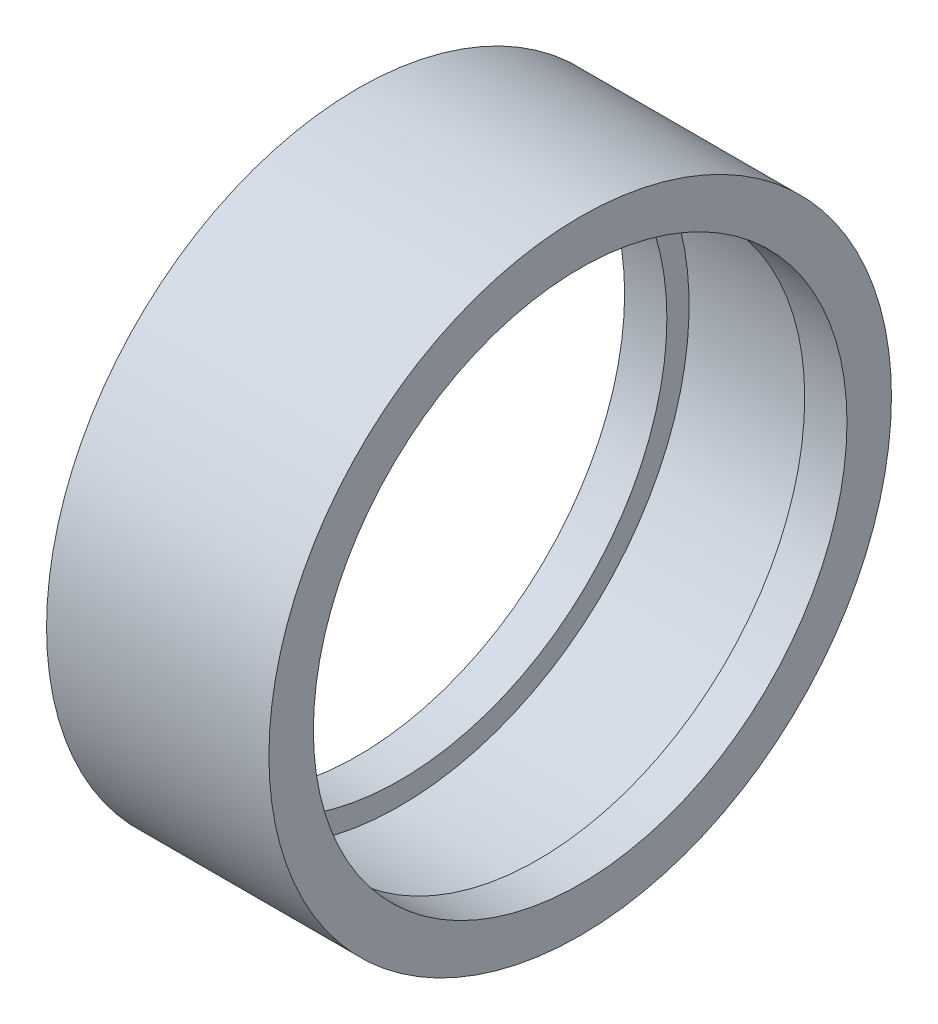
SolidWorks part; units mm, degrees
ref_plane "Front Plane" through (0, 0, 0) normal (0, 0, 1) x (1, 0, 0)
ref_plane "Top Plane" through (0, 0, 0) normal (0, 1, 0) x (1, 0, 0)
ref_plane "Right Plane" through (0, 0, 0) normal (1, 0, 0) x (0, 0, -1)
sketch "Sketch1" plane through (0, 0, 0) normal (0, 0, 1) x (1, 0, 0)
  line L0 (-182.7411, 0) -> (195.533, 0) construction
  line L1 (92.835, 60) -> (102.335, 60)
  line L2 (52.335, 70) -> (102.335, 70)
  line L3 (52.335, 70) -> (52.335, 60)
  line L4 (52.335, 60) -> (61.835, 60)
  line L5 (102.335, 70) -> (102.335, 60)
  line L6 (52.335, 70) -> (102.335, 60) construction
  line L7 (52.335, 60) -> (102.335, 70) construction
  line L8 (92.835, 65) -> (61.835, 65)
  line L9 (92.835, 65) -> (92.835, 60)
  line L11 (61.835, 65) -> (61.835, 60)
  line L12 (92.835, 65) -> (61.835, 60) construction
  line L13 (92.835, 60) -> (61.835, 65) construction
  point P3 (77.335, 65)
  point P8 (77.335, 62.5)
  dimension "D1" = 60
  dimension "D2" = 65
  dimension "D3" = 70
  dimension "D4" = 50
  dimension "D5" = 31
revolve "Revolve1" add sketch "Sketch1" angle 360 about L0
